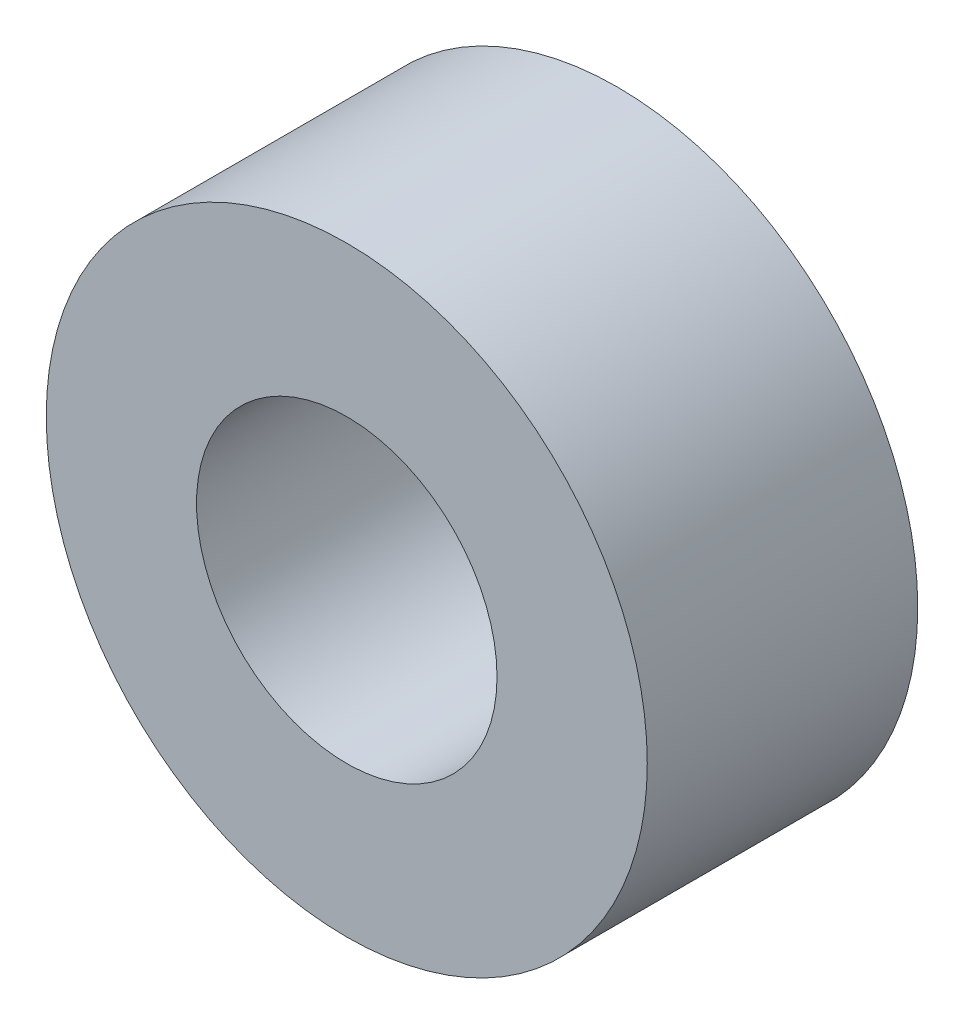
SolidWorks part; units mm, degrees
material "Brass"
ref_plane "Front Plane" through (0, 0, 0) normal (0, 0, 1) x (1, 0, 0)
ref_plane "Top Plane" through (0, 0, 0) normal (0, 1, 0) x (1, 0, 0)
ref_plane "Right Plane" through (0, 0, 0) normal (1, 0, 0) x (0, 0, -1)
sketch "Sketch1" plane through (0, 0, 0) normal (0, 0, 1) x (1, 0, 0)
  circle A0 centre (0, 0) radius 12.7
  dimension "D1" = 25.4
extrude "Boss-Extrude1" add sketch "Sketch1" along normal blind 11.43
sketch "Sketch2" plane through (0, 0, 11.43) normal (0, 0, 1) x (1, 0, 0)
  circle A0 centre (0, 0) radius 6.35
  dimension "D1" = 12.7
extrude "Cut-Extrude1" cut sketch "Sketch2" against normal through all
